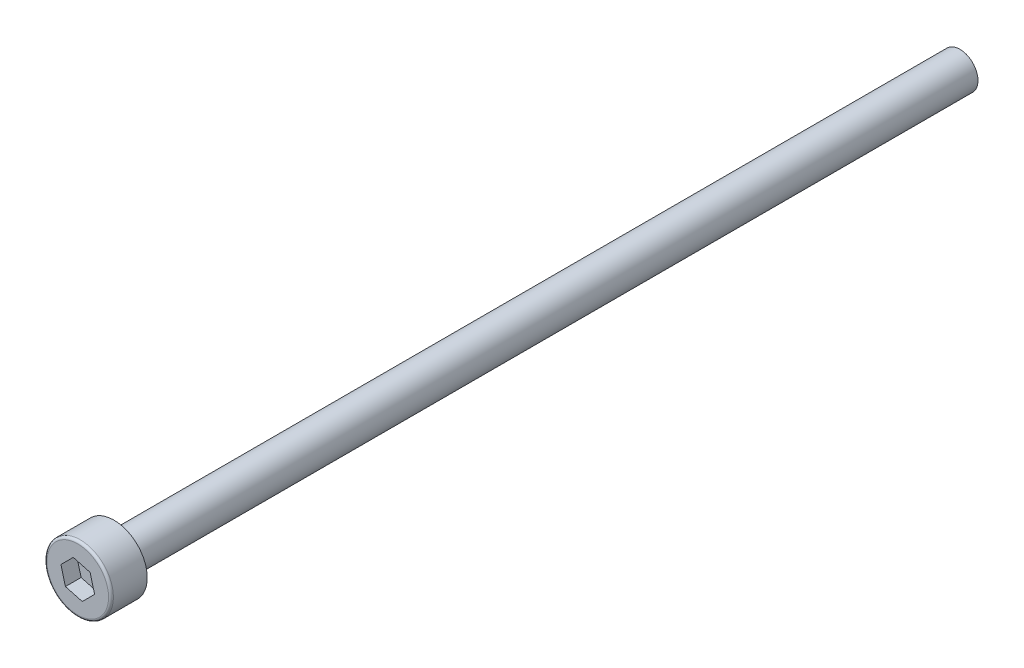
SolidWorks part; units mm, degrees
ref_plane "前视基准面" through (0, 0, 0) normal (0, 0, 1) x (1, 0, 0)
ref_plane "上视基准面" through (0, 0, 0) normal (0, 1, 0) x (1, 0, 0)
ref_plane "右视基准面" through (0, 0, 0) normal (1, 0, 0) x (0, 0, -1)
sketch "草图1" plane through (0, 0, 0) normal (0, 0, 1) x (1, 0, 0)
  circle A0 centre (0, 0) radius 2.75
  dimension "D1" = 5.5
extrude "凸台-拉伸1" add sketch "草图1" along normal blind 3
sketch "草图2" plane through (0, 0, 3) normal (0, 0, 1) x (1, 0, 0)
  line L1 (-1.0206, -1.0206) -> (0.3736, -1.3942)
  line L2 (0.3736, -1.3942) -> (1.3942, -0.3736)
  line L3 (1.3942, -0.3736) -> (1.0206, 1.0206)
  line L4 (1.0206, 1.0206) -> (-0.3736, 1.3942)
  line L5 (-0.3736, 1.3942) -> (-1.3942, 0.3736)
  line L6 (-1.3942, 0.3736) -> (-1.0206, -1.0206)
  circle A0 centre (0, 0) radius 1.25 construction
  dimension "D1" = 2.5
extrude "切除-拉伸1" cut sketch "草图2" against normal blind 1.3
sketch "草图3" plane through (0, 0, 0) normal (0, 0, -1) x (-1, 0, 0)
  circle A0 centre (0, 0) radius 1.5
  dimension "D1" = 3
extrude "凸台-拉伸2" add sketch "草图3" along normal blind 70
fillet "圆角1" radius 0.2 1 edges at (2.75, 0, 3)
